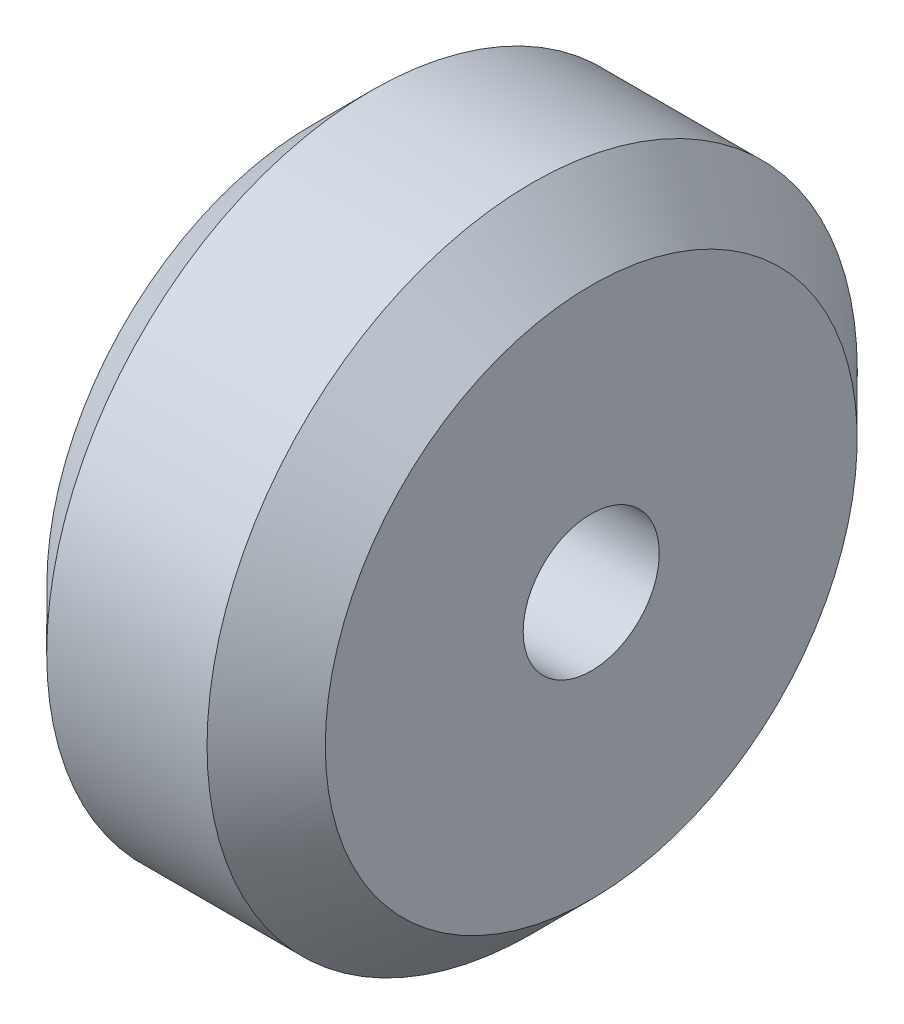
SolidWorks part; units mm, degrees
material "Caucho natural"
ref_plane "Alzado" through (0, 0, 0) normal (0, 0, 1) x (1, 0, 0)
ref_plane "Planta" through (0, 0, 0) normal (0, 1, 0) x (1, 0, 0)
ref_plane "Vista lateral" through (0, 0, 0) normal (1, 0, 0) x (0, 0, -1)
sketch "Croquis1" plane through (0, 0, 0) normal (0, 0, 1) x (1, 0, 0)
  line L0 (0, 0) -> (10.23, 0) construction
  line L1 (10.23, 2.5) -> (10.23, 9.77)
  line L2 (10.23, 9.77) -> (8.06, 11.945)
  line L3 (8.06, 11.945) -> (2.17, 11.945)
  line L4 (2.17, 11.945) -> (0, 9.77)
  line L5 (0, 9.77) -> (0, 2.5)
  line L6 (0, 2.5) -> (10.23, 2.5)
  point P3 (5.115, 11.945)
  point P8 (5.115, 0)
  dimension "D1" = 10.23
  dimension "D2" = 11.945
  dimension "D3" = 5.89
  dimension "D4" = 9.77
  dimension "D5" = 2.5
revolve "Revolución1" add sketch "Croquis1" angle 360 about L0
